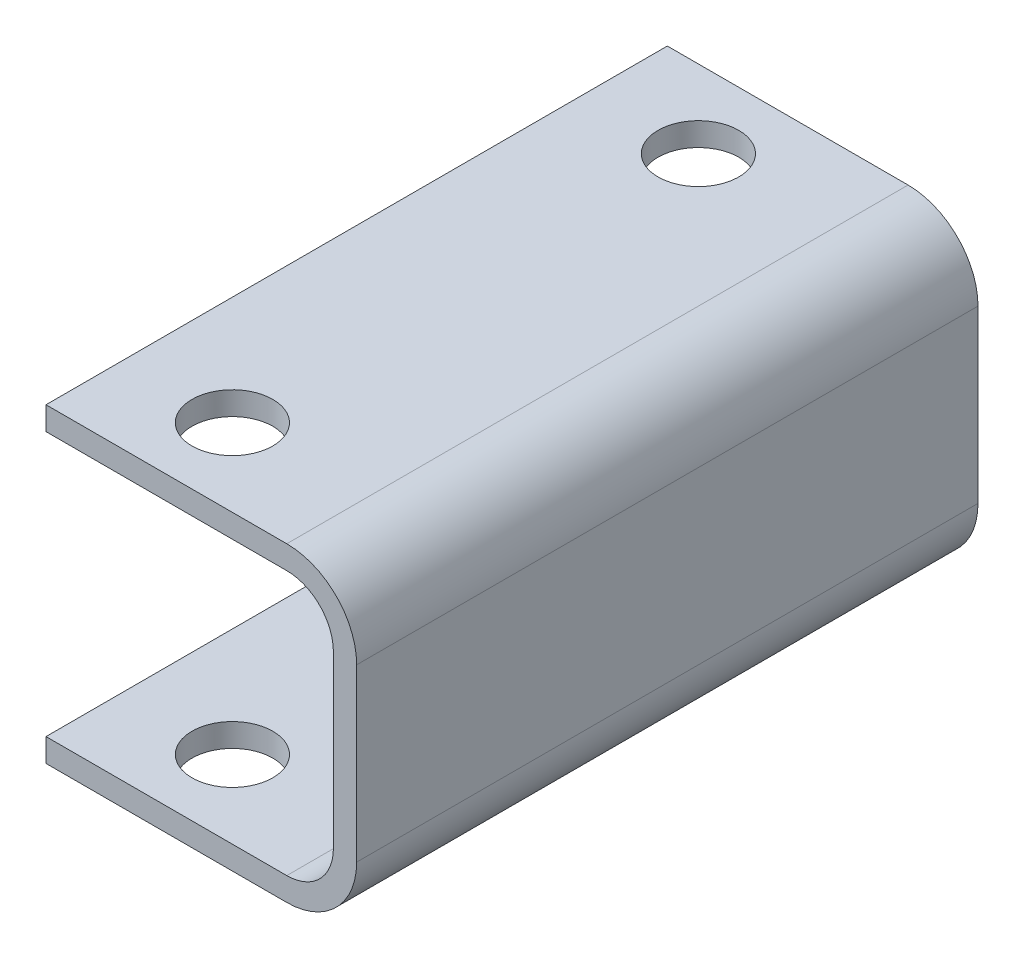
SolidWorks part; units mm, degrees
ref_plane "Ebene vorne" through (0, 0, 0) normal (1, 0, 0) x (0, 1, 0)
ref_plane "Ebene oben" through (0, 0, 0) normal (0, 0, 1) x (0, 1, 0)
ref_plane "Ebene rechts" through (0, 0, 0) normal (0, 1, 0) x (-1, 0, 0)
sketch "Skizze1" plane through (0, 0, 0) normal (0, 0, 1) x (0, 1, 0)
  line L0 (0, 0) -> (0, 14162.1429) construction
  line L1 (5.5, -5.4257) -> (-5.5, -5.4257)
  line L2 (-10, -0.9257) -> (-10, 14.5743)
  line L3 (-10, 14.5743) -> (-8.5, 14.5743)
  line L4 (-8.5, 14.5743) -> (-8.5, -0.9257)
  line L5 (-5.5, -3.9257) -> (5.5, -3.9257)
  line L6 (8.5, 14.5743) -> (8.5, -0.9257)
  line L7 (10, -0.9257) -> (10, 14.5743)
  line L8 (10, 14.5743) -> (8.5, 14.5743)
  arc A0 (-8.5, -0.9257) -> (-5.5, -3.9257) centre (-5.5, -0.9257) ccw
  arc A1 (-5.5, -5.4257) -> (-10, -0.9257) centre (-5.5, -0.9257) cw
  arc A2 (8.5, -0.9257) -> (5.5, -3.9257) centre (5.5, -0.9257) cw
  arc A3 (5.5, -5.4257) -> (10, -0.9257) centre (5.5, -0.9257) ccw
  point P14 (0, -5.4257)
  point P15 (0, -3.9257)
  dimension "D5" = 3
  dimension "D1" = 1.5
  dimension "D3" = 20
  dimension "D4" = 20
extrude "Aufsatz-Linear austragen1" add sketch "Skizze1" along normal blind 40
sketch "Skizze2" plane through (0, -10, 0) normal (0, -1, 0) x (1, 0, 0)
  line L0 (-14.5743, 0) -> (0.9257, 0) construction
  line L1 (-14.5743, 40) -> (0.9257, 40) construction
  line L3 (-14.5743, 40) -> (-14.5743, 0) construction
  circle A0 centre (-7.5743, 35) radius 2.6
  circle A1 centre (-7.5743, 5) radius 2.6
  dimension "D1" = 5.2
  dimension "D3" = 5.2
  dimension "4,5" = 5
  dimension "D2" = 7
  dimension "D4" = 7
  dimension "D5" = 5
extrude "Schnitt-Linear austragen1" cut sketch "Skizze2" against normal up to surface (20 mm away) up to face at (-6.8243, 10, 20)
equation "\"D4@Skizze2\"=\"D2@Skizze2\""
equation "\"D5@Skizze2\"=\"4,5@Skizze2\""
equation "\"D3@Skizze2\"=\"D1@Skizze2\""
